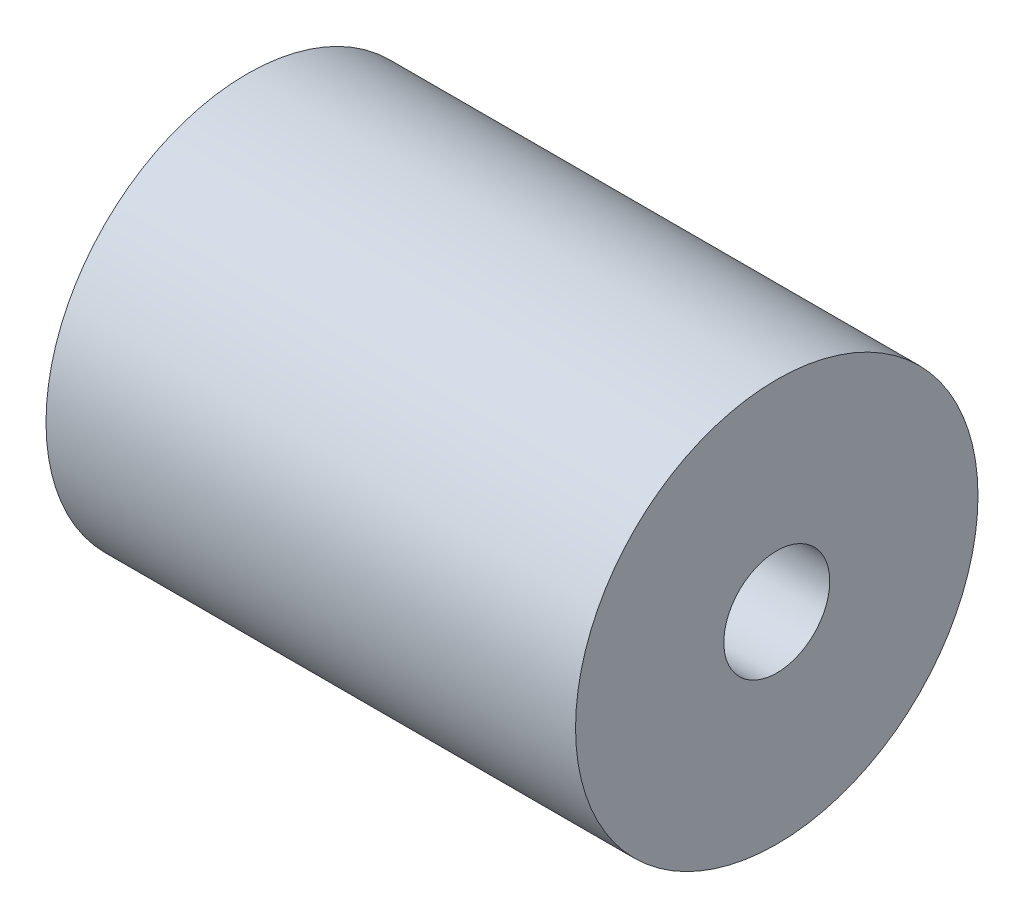
SolidWorks part; units mm, degrees
ref_plane "前视基准面" through (0, 0, 0) normal (0, 0, 1) x (1, 0, 0)
ref_plane "上视基准面" through (0, 0, 0) normal (0, 1, 0) x (1, 0, 0)
ref_plane "右视基准面" through (0, 0, 0) normal (1, 0, 0) x (0, 0, -1)
sketch "草图1" plane through (0, 0, 0) normal (1, 0, 0) x (0, 0, -1)
  circle A0 centre (-30.5168, 0) radius 9.5
extrude "凸台-拉伸1" add sketch "草图1" along normal blind 25
sketch "草图2" plane through (0, 0, 0) normal (-1, 0, 0) x (0, 0, 1)
  circle A0 centre (30.5168, 0) radius 4
extrude "切除-拉伸1" cut sketch "草图2" against normal blind 18
sketch "草图3" plane through (25, 0, 0) normal (1, 0, 0) x (0, 0, -1)
  line L0 (-30.5168, 9.5) -> (-30.5168, -9.5) construction
  circle A0 centre (-30.5168, 0) radius 9.5 construction
  circle A1 centre (-30.5168, 0) radius 2.5
extrude "切除-拉伸2" cut sketch "草图3" against normal blind 18
